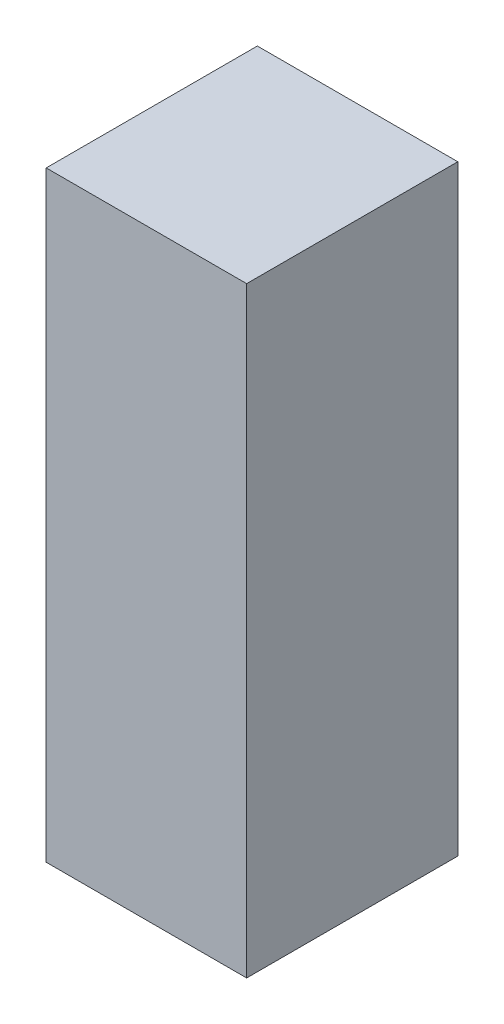
SolidWorks part; units mm, degrees
ref_plane "Front Plane" through (0, 0, 0) normal (0, 0, 1) x (1, 0, 0)
ref_plane "Top Plane" through (0, 0, 0) normal (0, 1, 0) x (1, 0, 0)
ref_plane "Right Plane" through (0, 0, 0) normal (1, 0, 0) x (0, 0, -1)
sketch "Sketch2" plane through (0, 0, 0) normal (1, 0, 0) x (0, 0, -1)
  line L1 (0, 0) -> (3.16, 0)
  line L2 (0, 0) -> (0, 9)
  line L3 (0, 9) -> (3.16, 9)
  line L4 (3.16, 0) -> (3.16, 9)
  dimension "D1" = 3.16
  dimension "D2" = 9
extrude "Boss-Extrude1" add sketch "Sketch2" along normal blind 3
